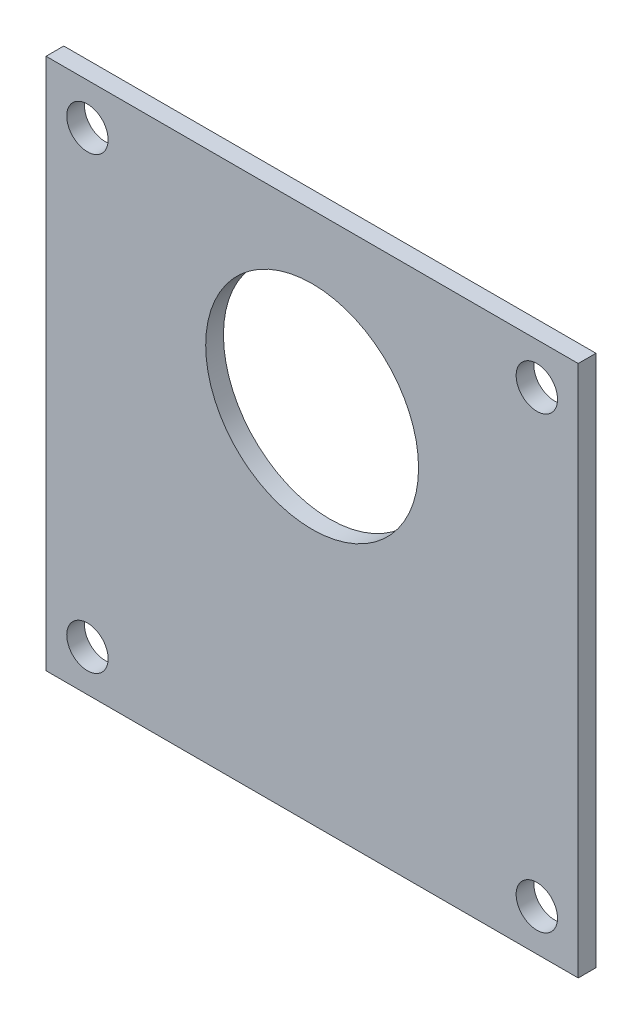
SolidWorks part; units mm, degrees
ref_plane "Front Plane" through (0, 0, 0) normal (0, 0, 1) x (1, 0, 0)
ref_plane "Top Plane" through (0, 0, 0) normal (0, 1, 0) x (1, 0, 0)
ref_plane "Right Plane" through (0, 0, 0) normal (1, 0, 0) x (0, 0, -1)
sketch "Sketch1" plane through (0, 0, 0) normal (0, 0, 1) x (1, 0, 0)
  line L1 (-22.5, 22.5) -> (22.5, 22.5)
  line L2 (-22.5, 22.5) -> (-22.5, -22.5)
  line L3 (-22.5, -22.5) -> (22.5, -22.5)
  line L4 (22.5, 22.5) -> (22.5, -22.5)
  line L5 (-22.5, 22.5) -> (22.5, -22.5) construction
  line L6 (-22.5, -22.5) -> (22.5, 22.5) construction
  point P0 (0, 0)
  dimension "D1" = 45
extrude "Boss-Extrude1" add sketch "Sketch1" along normal blind 1.5
sketch "Sketch2" plane through (0, 0, 1.5) normal (0, 0, 1) x (1, 0, 0)
  line L0 (0, 0) -> (12.6909, 0) construction
  line L1 (-19, 19) -> (19, 19) construction
  line L2 (-19, 19) -> (-19, -19) construction
  line L3 (-19, -19) -> (19, -19) construction
  line L4 (19, 19) -> (19, -19) construction
  line L5 (-19, 19) -> (19, -19) construction
  line L6 (-19, -19) -> (19, 19) construction
  line L7 (22.5, 22.5) -> (-22.5, 22.5) construction
  line L8 (0, 0) -> (0, 13.2971) construction
  circle A0 centre (-19, 19) radius 1.75
  circle A1 centre (19, -19) radius 1.75
  circle A2 centre (19, 19) radius 1.75
  circle A3 centre (-19, -19) radius 1.75
  circle A4 centre (0, 8.1) radius 9
  point P0 (0, 0)
  dimension "D2" = 3.5
  dimension "D3" = 14.4
  dimension "D4" = 18
  dimension "D1" = 38
extrude "Cut-Extrude1" cut sketch "Sketch2" against normal through all
